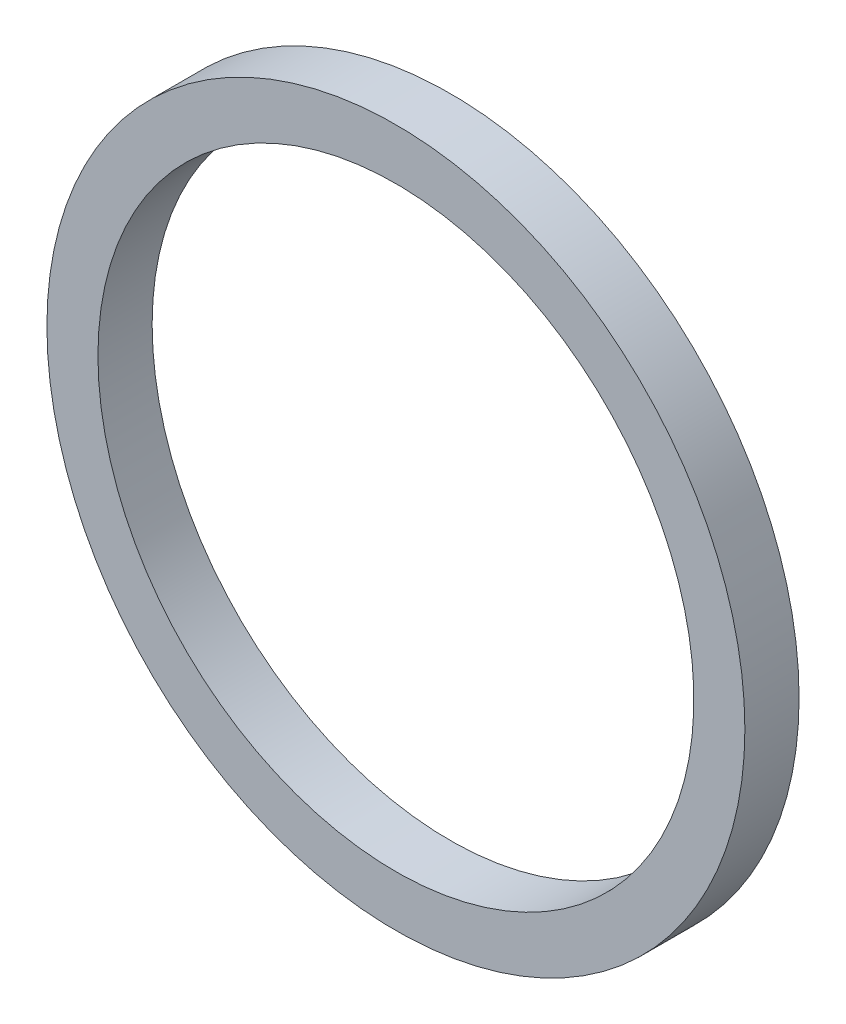
SolidWorks part; units mm, degrees
material "POLYURETHANE (11671)"
ref_plane "Front" through (0, 0, 0) normal (0, 0, 1) x (1, 0, 0)
ref_plane "Top" through (0, 0, 0) normal (0, 1, 0) x (1, 0, 0)
ref_plane "Right" through (0, 0, 0) normal (1, 0, 0) x (0, 0, -1)
sketch "Sketch1" plane through (0, 0, 0) normal (0, 0, 1) x (1, 0, 0)
  circle A0 centre (0, 0) radius 18.25
  circle A1 centre (0, 0) radius 21.375
  dimension "D1" = 42.75
  dimension "D2" = 36.5
extrude "Boss-Extrude1" add sketch "Sketch1" along normal blind 3.32
